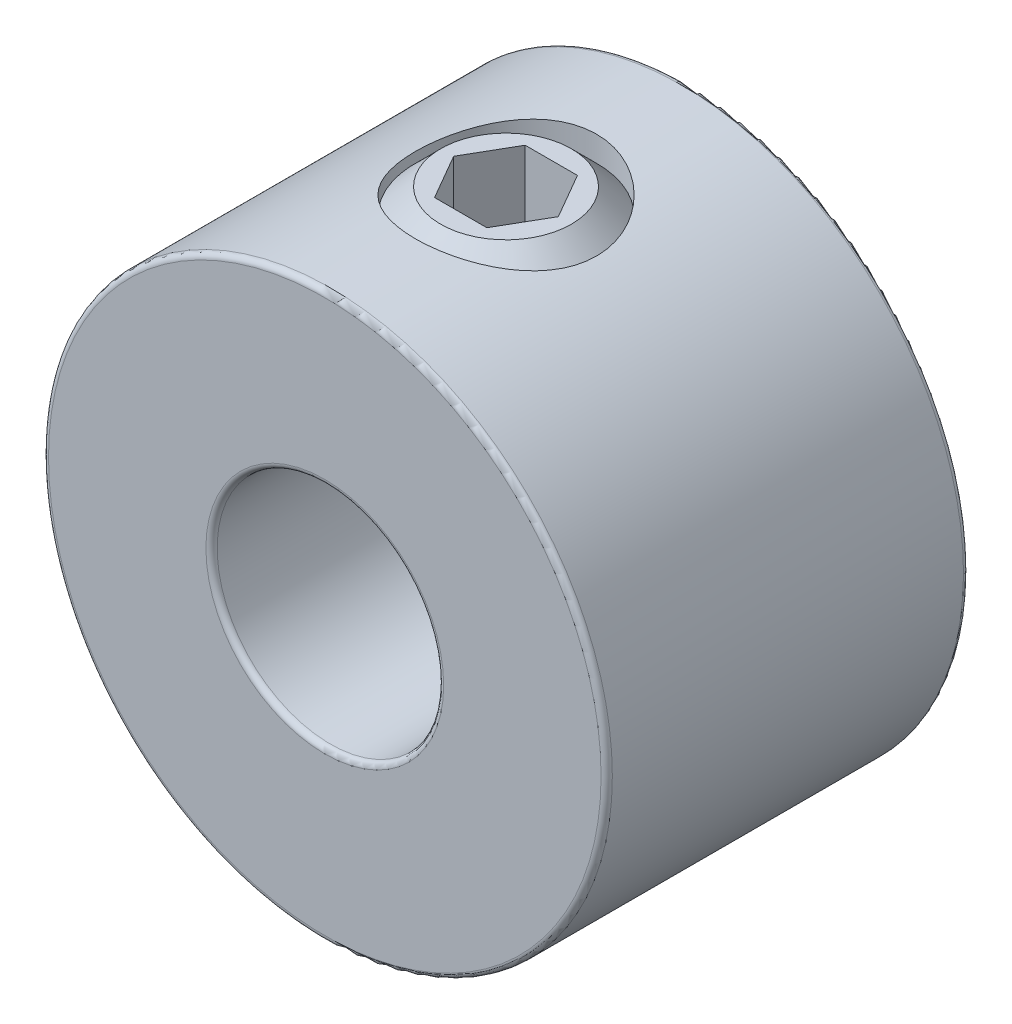
SolidWorks part; units mm, degrees
ref_plane "Front Plane" through (0, 0, 0) normal (0, 0, 1) x (1, 0, 0)
ref_plane "Top Plane" through (0, 0, 0) normal (0, 1, 0) x (1, 0, 0)
ref_plane "Right Plane" through (0, 0, 0) normal (1, 0, 0) x (0, 0, -1)
sketch "Sketch1" plane through (0, 0, 0) normal (0, 0, 1) x (1, 0, 0)
  circle A0 centre (0, 0) radius 6.223
  circle A1 centre (0, 0) radius 2.5
  point P4 (6.223, 0)
  point P5 (0, 6.223)
  dimension "Bore Dia" = 5
  dimension "OD" = 12.446
extrude "Extrude1" add sketch "Sketch1" along normal blind 8
ref_plane "Plane1" through (0, 6.223, 0) normal (0, 1, 0) x (-1, 0, 0)
sketch "Sketch2" plane through (0, 6.223, 0) normal (0, 1, 0) x (-1, 0, 0)
  line L0 (0, 0) -> (0, 8) construction
  line L2 (6.223, 8) -> (-6.223, 8) construction
  circle A0 centre (0, 4) radius 2
  dimension "Set Screw Dia" = 4
extrude "Cut-Extrude1" cut sketch "Sketch2" against normal up to surface (6.223 mm away) up to plane "Top Plane"
ref_plane "Plane2" through (0, 0, 4) normal (0, 0, 1) x (1, 0, 0)
sketch "Sketch3" plane through (0, 0, 4) normal (0, 0, 1) x (1, 0, 0)
  line L0 (-1.4434, 6.223) -> (-2, 5.6664)
  line L1 (0, 3.089) -> (0, 6.223)
  line L2 (-0.5, 2.223) -> (-1.4434, 2.223)
  line L3 (-2, 2.7796) -> (-2, 5.6664)
  line L4 (0, 6.223) -> (-1.4434, 6.223)
  line L5 (0, 2.223) -> (0, 0) construction
  line L6 (-2, 5.6664) -> (0, 5.6664) construction
  line L7 (0, 3.089) -> (-0.5, 2.223)
  line L8 (-1.4434, 2.223) -> (-2, 2.7796)
  point P1 (-0.5, 2.223)
  dimension "Screw Length" = 4
  dimension "D3" = 4
  dimension "D1" = 2.8868
  dimension "D7" = 2
  dimension "D8" = 0.5
  dimension "D2" = 45
  dimension "D4" = 45
  dimension "D5" = 60
revolve "Revolve1" add sketch "Sketch3" angle 360 about L1
sketch "Sketch4" plane through (0, 6.223, 0) normal (0, 1, 0) x (0, 0, -1)
  line L0 (-4, 1.1547) -> (-4, -1.1547) construction
  line L1 (-4, 1.1547) -> (-5, 0.5774)
  line L2 (-5, 0.5774) -> (-5, -0.5774)
  line L3 (-5, -0.5774) -> (-4, -1.1547)
  line L4 (-4, -1.1547) -> (-3, -0.5774)
  line L5 (-3, -0.5774) -> (-3, 0.5774)
  line L6 (-3, 0.5774) -> (-4, 1.1547)
  circle A0 centre (-4, 0) radius 1 construction
  circle A1 centre (-4, 0) radius 1.1547 construction
  dimension "D1" = 2.3094
  dimension "Hex" = 2
extrude "Cut-Extrude2" cut sketch "Sketch4" against normal blind 1.6
fillet "Fillet1" radius 0.1245 4 edges at (2.5, 0, 0) (2.5, 0, 8) (6.223, 0, 0) (6.223, 0, 8)
equation "\"D3@Sketch3\" = \"Set Screw Dia@Sketch2\""
equation "\"D1@Fillet1\" = \"OD@Sketch1\"*.01"
equation "\"D1@Sketch3\" = \"D1@Sketch4\"*1.25"
equation "\"D1@Cut-Extrude2\" = \"Hex@Sketch4\"*.8"
equation "\"D8@Sketch3\" = \"D7@Sketch3\"/4"
